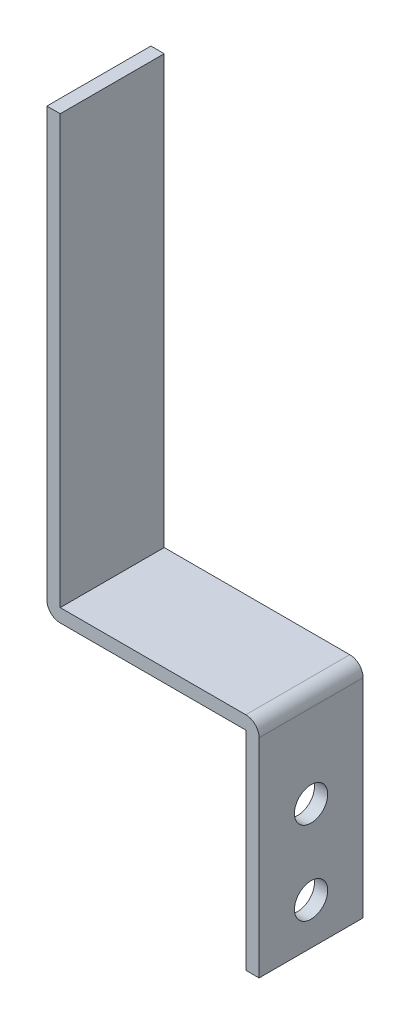
SolidWorks part; units mm, degrees
ref_plane "正面" through (0, 0, 0) normal (0, 0, 1) x (1, 0, 0)
ref_plane "平面" through (0, 0, 0) normal (0, 1, 0) x (1, 0, 0)
ref_plane "右側面" through (0, 0, 0) normal (1, 0, 0) x (0, 0, -1)
sketch "ｽｹｯﾁ1" plane through (0, 0, 0) normal (0, 0, 1) x (1, 0, 0)
  line L0 (0, 156) -> (0, 53.2)
  line L1 (3.2, 50) -> (47.8, 50)
  line L2 (47.8, 50) -> (47.8, 0)
  line L3 (47.8, 0) -> (51, 0)
  line L4 (51, 0) -> (51, 50)
  line L5 (47.8, 53.2) -> (3.2, 53.2)
  line L6 (3.2, 53.2) -> (3.2, 156)
  line L7 (3.2, 156) -> (0, 156)
  arc A0 (51, 50) -> (47.8, 53.2) centre (47.8, 50) ccw
  arc A1 (0, 53.2) -> (3.2, 50) centre (3.2, 53.2) ccw
  dimension "D1" = 3.2
extrude "ﾎﾞｽ - 押し出し1" add sketch "ｽｹｯﾁ1" along normal blind 25
sketch "ｽｹｯﾁ2" plane through (0, 0, 0) normal (1, 0, 0) x (0, 0, -1)
  circle A0 centre (10, 12.5) radius 4
  circle A1 centre (30, 12.5) radius 4
sketch "ｽｹｯﾁ3" plane through (0, 0, 0) normal (1, 0, 0) x (0, 0, -1)
  circle A0 centre (10, -12.5) radius 4
  circle A1 centre (30, -12.5) radius 4
sketch "ｽｹｯﾁ4" plane through (0, 0, 0) normal (1, 0, 0) x (0, 0, -1)
  circle A0 centre (10, 12.5) radius 4
  circle A1 centre (30, 12.5) radius 4
sketch "ｽｹｯﾁ6" plane through (0, 0, 0) normal (1, 0, 0) x (0, 0, -1)
  circle A0 centre (12.5, 10) radius 4
  circle A1 centre (12.5, 30) radius 4
sketch "ｽｹｯﾁ7" plane through (0, 0, 0) normal (1, 0, 0) x (0, 0, -1)
  circle A0 centre (-12.5, 10) radius 4
  circle A1 centre (-12.5, 30) radius 4
extrude "ｶｯﾄ - 押し出し5" cut sketch "ｽｹｯﾁ7" against normal through all and the other way through all
